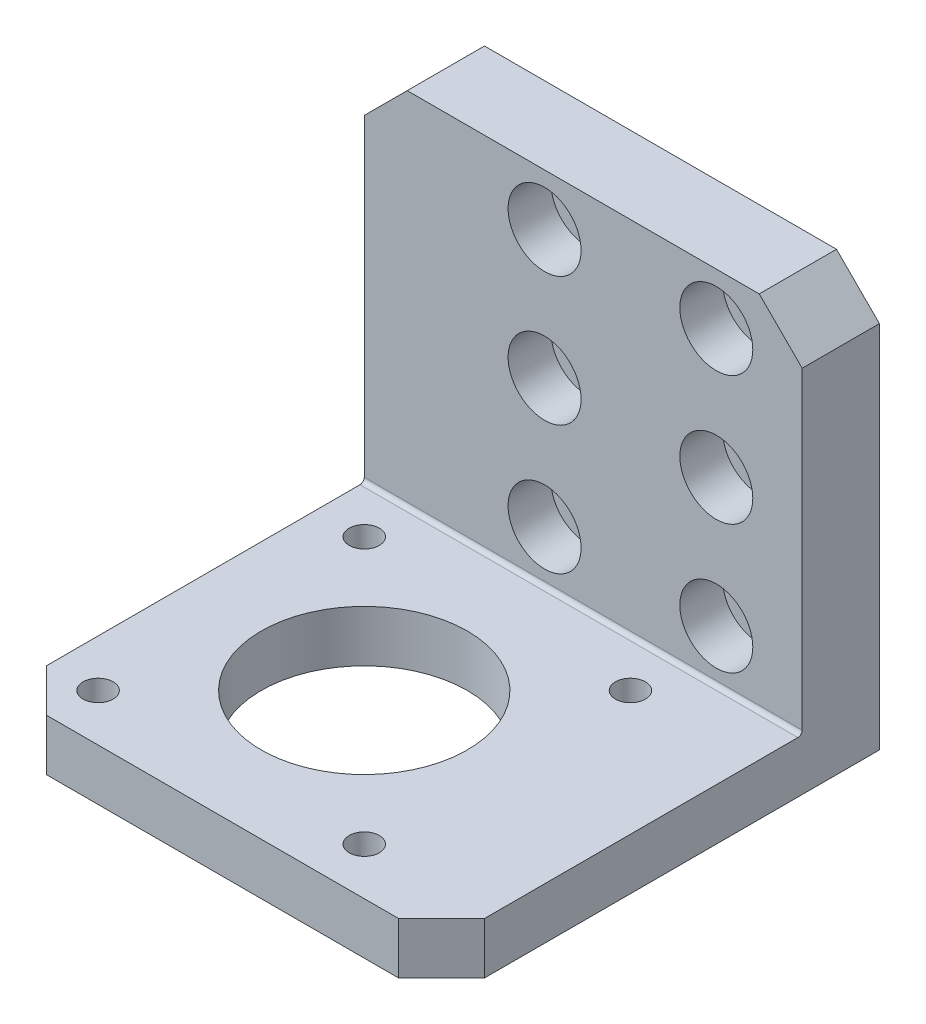
SolidWorks part; units mm, degrees
ref_plane "前基準面" through (0, 0, 0) normal (0, 0, 1) x (1, 0, 0)
ref_plane "上基準面" through (0, 0, 0) normal (0, 1, 0) x (1, 0, 0)
ref_plane "右基準面" through (0, 0, 0) normal (1, 0, 0) x (0, 0, -1)
sketch "草圖1" plane through (0, 0, 0) normal (0, 0, 1) x (1, 0, 0)
  line L0 (30, 21) -> (21, 21)
  line L1 (-21, 21) -> (21, 21)
  line L2 (-21, 21) -> (-21, -21)
  line L3 (-21, -21) -> (21, -21)
  line L4 (30, -21) -> (21, -21)
  line L9 (30, 21) -> (30, -21)
  circle A0 centre (0, 15) radius 2.75
  circle A1 centre (20, 15) radius 2.75
  circle A2 centre (20, 0) radius 2.75
  circle A3 centre (20, -15) radius 2.75
  circle A4 centre (0, 0) radius 2.75
  circle A5 centre (0, -15) radius 2.75
  point P4 (0, 21)
  point P6 (-21, 0)
  dimension "D3" = 5.5
  dimension "D4" = 6
  dimension "D7" = 6
  dimension "D1" = 42
  dimension "D2" = 42
  dimension "D5" = 2
  dimension "D10" = 10
  dimension "D6" = 3
extrude "填料-伸長1" add sketch "草圖1" along normal blind 9
sketch "草圖3" plane through (0, -21, 0) normal (0, -1, 0) x (1, 0, 0)
  line L1 (-21, 9) -> (21, 9)
  line L2 (-21, 9) -> (-21, 51)
  line L3 (-21, 51) -> (21, 51)
  line L4 (21, 9) -> (21, 51)
  line L6 (0, 51) -> (0, 9) construction
  line L7 (-21, 30) -> (21, 30) construction
  circle A0 centre (-15.5, 45.5) radius 1.75
  circle A1 centre (-15.5, 14.5) radius 1.75
  circle A2 centre (15.5, 14.5) radius 1.75
  circle A3 centre (15.5, 45.5) radius 1.75
  circle A4 centre (0, 30) radius 12
  dimension "D3" = 3.5
  dimension "D6" = 24
  dimension "D1" = 42
  dimension "D2" = 42
  dimension "D4" = 5.5
  dimension "D5" = 5.5
extrude "填料-伸長2" add sketch "草圖3" along normal blind 6 separate body
sketch "草圖4" plane through (0, -27, 0) normal (0, -1, 0) x (1, 0, 0)
  line L0 (0, 51) -> (0, 9) construction
  line L1 (21, 51) -> (-21, 51) construction
  line L3 (0, 9) -> (21, 30) construction
  line L4 (21, 9) -> (21, 51) construction
  line L5 (21, 30) -> (-21, 30) construction
  line L6 (-21, 51) -> (-21, 9) construction
  circle A0 centre (-15.5, 45.5) radius 3
  circle A1 centre (-15.5, 14.5) radius 3
  circle A2 centre (15.5, 14.5) radius 3
  circle A3 centre (15.5, 45.5) radius 3
  dimension "D1" = 6
extrude "除料-伸長2" cut sketch "草圖4" against normal blind 3
sketch "草圖5" plane through (0, -21, 0) normal (0, -1, 0) x (1, 0, 0)
  line L0 (-21, 0) -> (30, 0) construction
  line L1 (-21, 9) -> (21, 9)
  line L2 (-21, 9) -> (-21, 0)
  line L3 (-21, 0) -> (21, 0)
  line L4 (21, 9) -> (21, 0)
extrude "填料-伸長3" add sketch "草圖5" along normal up to surface (6 mm away) up to face at (-15.5, -27, 17.5)
sketch "草圖6" plane through (0, 0, 9) normal (0, 0, 1) x (1, 0, 0)
  circle A0 centre (0, 15) radius 4.25
  circle A1 centre (20, 15) radius 4.25
  circle A2 centre (20, 0) radius 4.25
  circle A3 centre (20, -15) radius 4.25
  circle A4 centre (0, 0) radius 4.25
  circle A5 centre (0, -15) radius 4.25
  dimension "D1" = 8.5
  dimension "D2" = 2
  dimension "D3" = 3
extrude "除料-伸長3" cut sketch "草圖6" against normal blind 5
chamfer "導角2" distance 5 angle 45 2 edges at (-21, 21, 4.5) (30, 21, 4.5)
sketch "草圖7" plane through (21, 0, 0) normal (1, 0, 0) x (0, 0, -1)
  line L1 (-51, -27) -> (0, -27)
  line L2 (-51, -27) -> (-51, -21)
  line L3 (-51, -21) -> (0, -21)
  line L4 (0, -27) -> (0, -21)
extrude "填料-伸長4" add sketch "草圖7" along normal up to surface (9 mm away) up to face at (30, -2.5, 4.5)
chamfer "導角3" distance 5 angle 45 2 edges at (-21, -24, 51) (30, -24, 51)
fillet "圓角1" radius 0.5 1 edges at (4.5, -21, 9)
